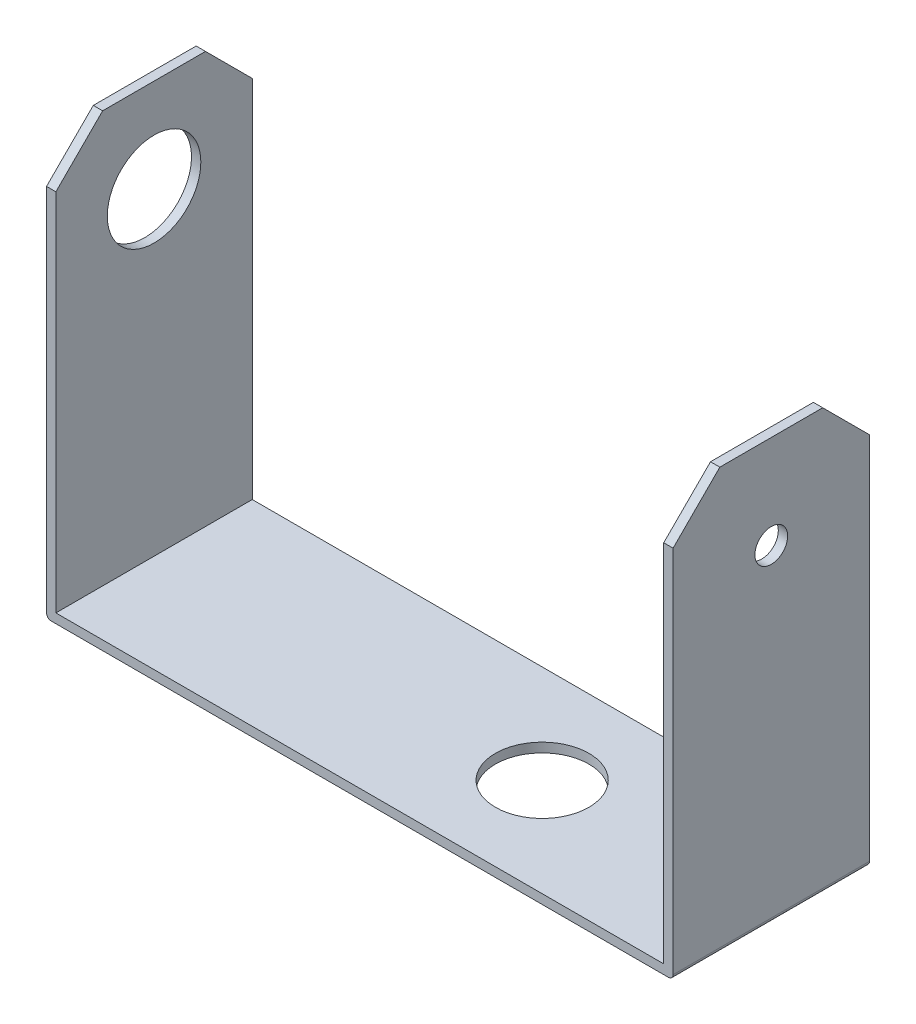
SolidWorks part; units mm, degrees
ref_plane "前视基准面" through (0, 0, 0) normal (0, 0, 1) x (1, 0, 0)
ref_plane "上视基准面" through (0, 0, 0) normal (0, 1, 0) x (1, 0, 0)
ref_plane "右视基准面" through (0, 0, 0) normal (1, 0, 0) x (0, 0, -1)
sketch "草图1" plane through (0, 0, 0) normal (0, 1, 0) x (1, 0, 0)
  line L0 (0, 0) -> (-67, 0)
  line L1 (-67, 0) -> (-67, 21)
  line L2 (-67, 21) -> (0, 21)
  line L3 (0, 21) -> (0, 0)
  dimension "D1" = 67
  dimension "D2" = 21
extrude "凸台-拉伸1" add sketch "草图1" along normal blind 45
shell "抽壳1" thickness 1
fillet "圆角1" radius 0.5 2 edges at (0, 0, -10.5) (-67, 0, -10.5)
chamfer "倒角1" distance 5 distance2 5 4 edges at (-66.5, 45, -21) (-66.5, 45, 0) (-0.5, 45, -21) (-0.5, 45, 0)
hole_wizard "Ø10.0 (10) 直径槽口1" positions "草图2" profile "草图3" size "Ø10.0" standard "GB"
sketch "草图2" plane through (-67, 0, 0) normal (-1, 0, 0) x (0, 0, 1)
  line L0 (-16, 45) -> (-5, 45) construction
  line L2 (0, 40) -> (0, 0.5) construction
  point P0 (-10.5, 35)
  point P9 (0, 35.154)
  point P16 (-59.5402, 40.8841)
  dimension "D1" = 10
  dimension "D2" = 10.5
sketch "草图3" plane through (-67, 35, -10.5) normal (0, 1, 0) x (0, 0, 1)
  line L0 (0, 0) -> (0, 1)
  line L1 (0, 1) -> (5, 1)
  line L2 (5, 1) -> (5, 0)
  line L5 (5, 0) -> (0, 0)
  line L11 (0, -6.35) -> (0, 107.95) construction
  dimension "通孔孔直径" = 10
  dimension "通孔孔深度" = 1
hole_wizard "Ø10.0 (10) 直径槽口2" positions "草图4" profile "草图5" size "Ø10.0" standard "GB" slot yes end condition up to next
sketch "草图4" plane through (0, 1, 0) normal (0, 1, 0) x (1, 0, 0)
  line L0 (-1, 0) -> (-1, 21) construction
  line L1 (-66, 0) -> (-1, 0) construction
  point P0 (-24.5, 10.5)
  point P9 (-93.1074, 34.3979)
  dimension "D1" = 23.5
  dimension "D2" = 10.5
sketch "草图5" plane through (-24.5, 1, -10.5) normal (1, 0, 0) x (0, 0, 1)
  line L0 (0, 0) -> (0, 1)
  line L1 (0, 1) -> (5, 1)
  line L2 (5, 1) -> (5, 0)
  line L5 (5, 0) -> (0, 0)
  line L11 (0, -6.35) -> (0, 107.95) construction
  dimension "通孔孔直径" = 10
  dimension "通孔孔深度" = 1
hole_wizard "Ø3.5 (3.5) 直径槽口1" positions "草图6" profile "草图7" size "Ø3.5" standard "GB" slot yes end condition up to next
sketch "草图6" plane through (0, 0, 0) normal (1, 0, 0) x (0, 0, -1)
  line L0 (5, 45) -> (16, 45) construction
  line L1 (0, 40) -> (0, 0.5) construction
  point P0 (10.5, 35)
  dimension "D1" = 10
  dimension "D2" = 10.5
sketch "草图7" plane through (0, 35, -10.5) normal (0, 1, 0) x (0, 0, -1)
  line L0 (0, 0) -> (0, 1)
  line L1 (0, 1) -> (1.75, 1)
  line L2 (1.75, 1) -> (1.75, 0)
  line L5 (1.75, 0) -> (0, 0)
  line L11 (0, -6.35) -> (0, 107.95) construction
  dimension "通孔孔直径" = 3.5
  dimension "通孔孔深度" = 1
